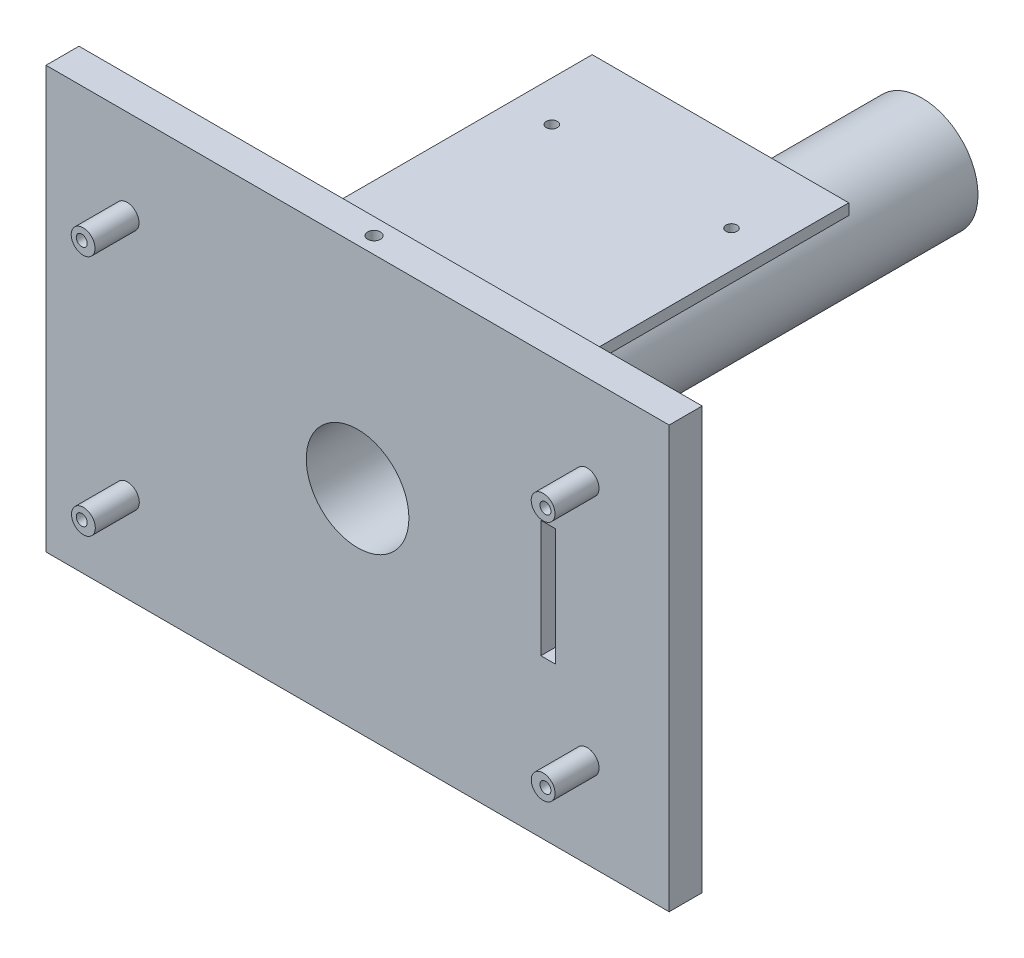
SolidWorks part; units mm, degrees
ref_plane "Plan de face" through (0, 0, 0) normal (0, 0, 1) x (1, 0, 0)
ref_plane "Plan de dessus" through (0, 0, 0) normal (0, 1, 0) x (1, 0, 0)
ref_plane "Plan de droite" through (0, 0, 0) normal (1, 0, 0) x (0, 0, -1)
sketch "Esquisse1" plane through (0, 0, 0) normal (0, 0, 1) x (1, 0, 0)
  line L0 (-7.4389, 13.3126) -> (7.4389, -13.3126) construction
  circle A0 centre (0, 0) radius 15.25
  circle A1 centre (0, 0) radius 13.5
  dimension "D1" = 30.5
  dimension "D2" = 27
extrude "Boss.-Extru.1" add sketch "Esquisse1" along normal blind 145
sketch "Esquisse4" plane through (0, 0, 0) normal (0, 1, 0) x (1, 0, 0)
  line L0 (-15.25, -145) -> (15.25, -145) construction
  circle A0 centre (0, -52.5) radius 2
  dimension "D1" = 4
  dimension "D2" = 92.5
extrude "Enlèv. mat.-Extru.1" cut sketch "Esquisse4" against normal up to next and the other way through all
sketch "Esquisse5" plane through (0, 0, 145) normal (0, 0, 1) x (1, 0, 0)
  line L0 (-85, 57.5) -> (85, -57.5) construction
  line L1 (-85, 57.5) -> (85, 57.5)
  line L2 (-85, 57.5) -> (-85, -57.5)
  line L3 (-85, -57.5) -> (85, -57.5)
  line L4 (85, 57.5) -> (85, -57.5)
  line L5 (-85, -57.5) -> (85, 57.5) construction
  line L6 (-9.632, 9.4591) -> (9.632, -9.4591) construction
  line L7 (9.0812, 9.9891) -> (-9.0812, -9.9891) construction
  circle A0 centre (0, 0) radius 13.5 construction
  point P12 (0, 0)
  point P13 (0, 0)
  point P14 (0, 0)
  dimension "D1" = 170
  dimension "D2" = 115
extrude "Boss.-Extru.2" add sketch "Esquisse5" along normal blind 9
sketch "Esquisse14" plane through (0, 0, 0) normal (0, 0, 1) x (1, 0, 0)
  circle A0 centre (0, 0) radius 14
  dimension "D1" = 28
extrude "Enlèv. mat.-Extru.2" cut sketch "Esquisse14" along normal through all
sketch "Esquisse15" plane through (0, 0, 154) normal (0, 0, 1) x (1, 0, 0)
  line L0 (-63.25, 33) -> (-63.25, -33) construction
  line L1 (-63.25, -33) -> (63.25, -33) construction
  line L2 (63.25, -33) -> (63.25, 33) construction
  line L3 (63.25, 33) -> (-63.25, 33) construction
  line L4 (-63.25, 33) -> (63.25, -33) construction
  line L5 (-63.25, -33) -> (63.25, 33) construction
  line L6 (-9.4581, 10.322) -> (9.4581, -10.322) construction
  line L7 (11.1434, 8.475) -> (-11.1434, -8.475) construction
  circle A0 centre (0, 0) radius 14 construction
  circle A1 centre (-63.25, 33) radius 1.5
  circle A2 centre (63.25, 33) radius 1.5
  circle A3 centre (63.25, -33) radius 1.5
  circle A4 centre (-63.25, -33) radius 1.5
  point P14 (0, 0)
  point P15 (0, 0)
  point P16 (0, 0)
  dimension "D3" = 3
  dimension "D1" = 126.5
  dimension "D2" = 66
extrude "Enlèv. mat.-Extru.3" cut sketch "Esquisse15" against normal through all and the other way through all
sketch "Esquisse16" plane through (0, 57.5, 0) normal (0, 1, 0) x (1, 0, 0)
  line L0 (-85, -154) -> (85, -145) construction
  line L1 (85, -154) -> (-85, -145) construction
  circle A0 centre (0, -149.5) radius 1.75
  point P6 (0, -149.5)
  dimension "D1" = 3.5
extrude "Enlèv. mat.-Extru.4" cut sketch "Esquisse16" against normal blind 15
sketch "Esquisse22" plane through (0, 0, 145) normal (0, 0, -1) x (-1, 0, 0)
  line L0 (0, 32.5) -> (0, 35.5) construction
  line L1 (-35, 32.5) -> (35, 32.5)
  line L2 (-35, 32.5) -> (-35, 35.5)
  line L3 (-35, 35.5) -> (35, 35.5)
  line L4 (35, 32.5) -> (35, 35.5)
  line L9 (-85, -57.5) -> (-85, 57.5) construction
  line L10 (0, 32.5) -> (0, 57.5) construction
  line L11 (-85, 57.5) -> (85, 57.5) construction
  dimension "D1" = 3
  dimension "D2" = 85
  dimension "D3" = 70
  dimension "D4" = 25
extrude "Boss.-Extru.11" add sketch "Esquisse22" along normal blind 90
sketch "Esquisse23" plane through (0, 35.5, 0) normal (0, 1, 0) x (1, 0, 0)
  line L0 (35, -55) -> (35, -145) construction
  line L1 (25, -77) -> (-24, -77)
  line L2 (25, -77) -> (25, -135)
  line L3 (25, -135) -> (-24, -135)
  line L4 (-24, -77) -> (-24, -135)
  line L7 (-35, -145) -> (35, -145) construction
  circle A4 centre (25, -77) radius 1.5
  circle A5 centre (-24, -77) radius 1.5
  circle A6 centre (-24, -135) radius 1.5
  circle A7 centre (25, -135) radius 1.5
  dimension "D4" = 49
  dimension "D7" = 3
  dimension "D1" = 49
  dimension "D2" = 58
  dimension "D3" = 58
  dimension "D5" = 10
  dimension "D6" = 10
extrude "Enlèv. mat.-Extru.6" cut sketch "Esquisse23" against normal blind 90 contours L3 A7 L2 | L2 A7 L3 | L4 A6 L3 | L3 A6 L4 | L1 A4 L2 | L2 A4 L1 | L1 A5 L4 | L4 A5 L1
sketch "Esquisse25" plane through (0, 0, 145) normal (0, 0, -1) x (-1, 0, 0)
  line L0 (-85, 57.5) -> (85, 57.5) construction
  line L1 (-54, 17.5) -> (-50, 17.5)
  line L2 (-54, 17.5) -> (-54, -14.5)
  line L3 (-54, -14.5) -> (-50, -14.5)
  line L4 (-50, 17.5) -> (-50, -14.5)
  line L5 (85, 57.5) -> (85, -57.5) construction
  dimension "D1" = 32
  dimension "D2" = 4
  dimension "D3" = 40
  dimension "D4" = 135
extrude "Enlèv. mat.-Extru.7" cut sketch "Esquisse25" against normal blind 90
sketch "Esquisse26" plane through (0, 0, 0) normal (0, 1, 0) x (1, 0, 0)
  line L1 (7.1868, -77.1073) -> (-8.7735, -77.1073)
  line L2 (7.1868, -77.1073) -> (7.1868, -59.8664)
  line L3 (7.1868, -59.8664) -> (-8.7735, -59.8664)
  line L4 (-8.7735, -77.1073) -> (-8.7735, -59.8664)
extrude "Enlèv. mat.-Extru.8" cut sketch "Esquisse26" along normal up to next
sketch "Esquisse27" plane through (0, 0, 154) normal (0, 0, 1) x (1, 0, 0)
  circle A0 centre (62.616, 32.9338) radius 3.25
  circle A1 centre (62.6223, -33.123) radius 3.25
  circle A2 centre (-62.8001, -33.0845) radius 3.25
  circle A3 centre (-62.8725, 32.9302) radius 3.25
  dimension "D1" = 6.5
  dimension "D2" = 6.5
  dimension "D3" = 6.5
  dimension "D4" = 6.5
extrude "Boss.-Extru.12" add sketch "Esquisse27" along normal blind 12
sketch "Esquisse29" plane through (0, 0, 145) normal (0, 0, -1) x (-1, 0, 0)
  line L3 (-63.25, 33) -> (63.25, 33)
  line L4 (-63.25, 33) -> (-63.25, -33)
  line L5 (-63.25, -33) -> (63.25, -33)
  line L6 (63.25, 33) -> (63.25, -33)
  circle A0 centre (-63.25, 33) radius 1.5
  circle A1 centre (63.25, 33) radius 1.5
  circle A2 centre (63.25, -33) radius 1.5
  circle A3 centre (-63.25, -33) radius 1.5
  point P4 (0, 0)
  point P8 (0, 0)
  point P12 (0, 0)
  point P14 (0, 0)
  point P16 (0, 0)
  point P21 (0, 0)
  circle M12 centre (-63.25, 33) radius 1.5
  circle M13 centre (63.25, -33) radius 1.5
  circle M14 centre (63.25, 33) radius 1.5
  circle M15 centre (-63.25, -33) radius 1.5
  dimension "D1" = 3
  dimension "D2" = 3
  dimension "D3" = 3
  dimension "D4" = 3
  dimension "D5" = 126.5
  dimension "D6" = 66
extrude "Enlèv. mat.-Extru.9" cut sketch "Esquisse29" against normal through all contours L3 L6 M14 | L6 L3 M14 | L6 L5 M13 | L6 L5 M13 | L4 L3 M12 | L3 L4 M12 | L5 L4 M15 | L4 L5 M15
